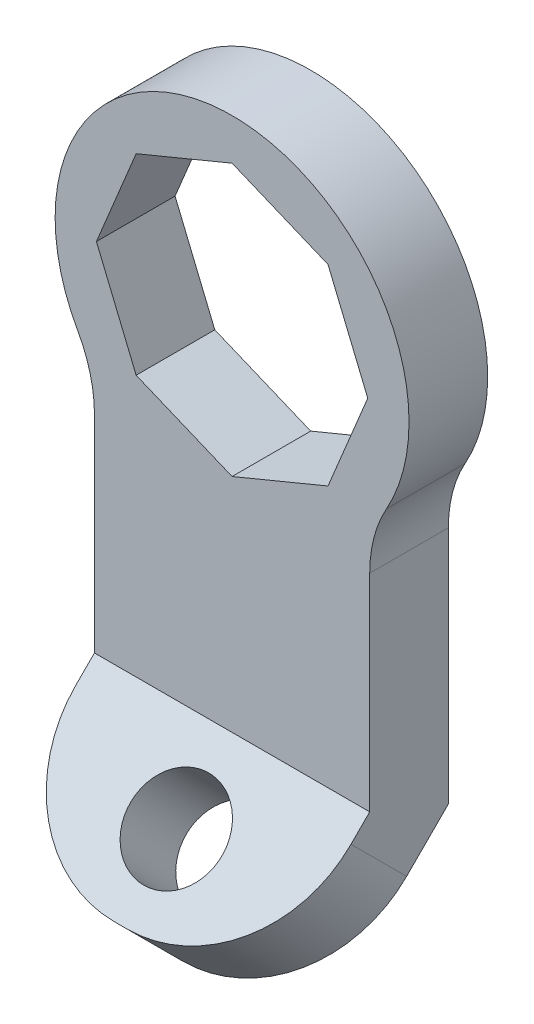
SolidWorks part; units mm, degrees
material "ABS"
ref_plane "前视基准面" through (0, 0, 0) normal (0, 0, 1) x (1, 0, 0)
ref_plane "上视基准面" through (0, 0, 0) normal (0, 1, 0) x (1, 0, 0)
ref_plane "右视基准面" through (0, 0, 0) normal (1, 0, 0) x (0, 0, -1)
sketch "草图1" plane through (0, 0, 0) normal (0, 0, 1) x (1, 0, 0)
  line L0 (10.35, 0) -> (7.3186, -7.3186)
  line L1 (7.3186, -7.3186) -> (0, -10.35)
  line L2 (0, -10.35) -> (-7.3186, -7.3186)
  line L3 (-7.3186, -7.3186) -> (-10.35, 0)
  line L4 (-10.35, 0) -> (-7.3186, 7.3186)
  line L5 (-7.3186, 7.3186) -> (0, 10.35)
  line L6 (0, 10.35) -> (7.3186, 7.3186)
  line L7 (7.3186, 7.3186) -> (10.35, 0)
  circle A0 centre (0, 0) radius 10.35 construction
  circle A1 centre (0, 0) radius 13.5
  dimension "D1" = 20.7
  dimension "D2" = 27
extrude "凸台-拉伸1" add sketch "草图1" along normal blind 6 contours A0 | A1 | L7 L0 L1 L2 L3 L4 L5 L6
sketch "草图2" plane through (0, 0, 6) normal (0, 0, 1) x (1, 0, 0)
  line L1 (-10.5, -30) -> (10.5, -30)
  line L2 (-10.5, -30) -> (-10.5, 9.3)
  line L3 (-10.5, 9.3) -> (10.5, 9.3)
  line L4 (10.5, -30) -> (10.5, 9.3)
  line L5 (-10.5, -30) -> (10.5, 9.3) construction
  line L6 (-10.5, 9.3) -> (10.5, -30) construction
  point P0 (0, -10.35)
  circle M11 centre (0, 0) radius 13.5
  dimension "D1" = 21
  dimension "D2" = 30
extrude "凸台-拉伸2" add sketch "草图2" against normal blind 6 contours L1 L4 L2 M11
sketch "草图4" plane through (10.5, 0, 0) normal (1, 0, 0) x (0, 0, -1)
  line L0 (-6, -27.2574) -> (-14.5, -35.7574)
  line L1 (-6, -30) -> (-6, -8.4853) construction
  line L2 (-14.5, -35.7574) -> (-10.2574, -40)
  line L3 (-10.2574, -40) -> (0, -29.7426)
  line L4 (0, -29.7426) -> (-6, -27.2574)
  line L5 (0, -30) -> (-6, -30) construction
  line L6 (0, -30) -> (0, -8.4853) construction
  dimension "D1" = 8.5
  dimension "D2" = 6
  dimension "D3" = 45
  dimension "D4" = 10
extrude "凸台-拉伸3" add sketch "草图4" against normal blind 21
sketch "草图5" plane through (0, -10.6287, -10.6287) normal (0, 0.7071, 0.7071) x (1, 0, 0)
  line L0 (0, -35.5373) -> (0, -23.5165) construction
  line L1 (-10.5, -35.5373) -> (10.5, -35.5373) construction
  line L2 (-10.5, -23.5165) -> (10.5, -23.5165) construction
  circle A0 centre (0, -29.5373) radius 3.5
  dimension "D1" = 7
  dimension "D2" = 6
extrude "切除-拉伸1" cut sketch "草图5" against normal through all
sketch "草图6" plane through (10.5, 0, 0) normal (1, 0, 0) x (0, 0, -1)
  line L0 (-0.2574, -30) -> (0, -29.7426)
  line L1 (0, -30) -> (0, -8.4853) construction
  line M6 (-0.2574, -30) -> (0, -30)
  line M7 (0, -30) -> (0, -8.4853)
  dimension "D1" = 45
extrude "切除-拉伸3" cut sketch "草图6" against normal through all and the other way through all contours L0 M6 M7
fillet "圆角3" radius 10 4 edges at (10.5, -37.8787, 12.3787) (-10.5, -37.8787, 12.3787) (-10.5, -8.4853, 3) (10.5, -8.4853, 3)
